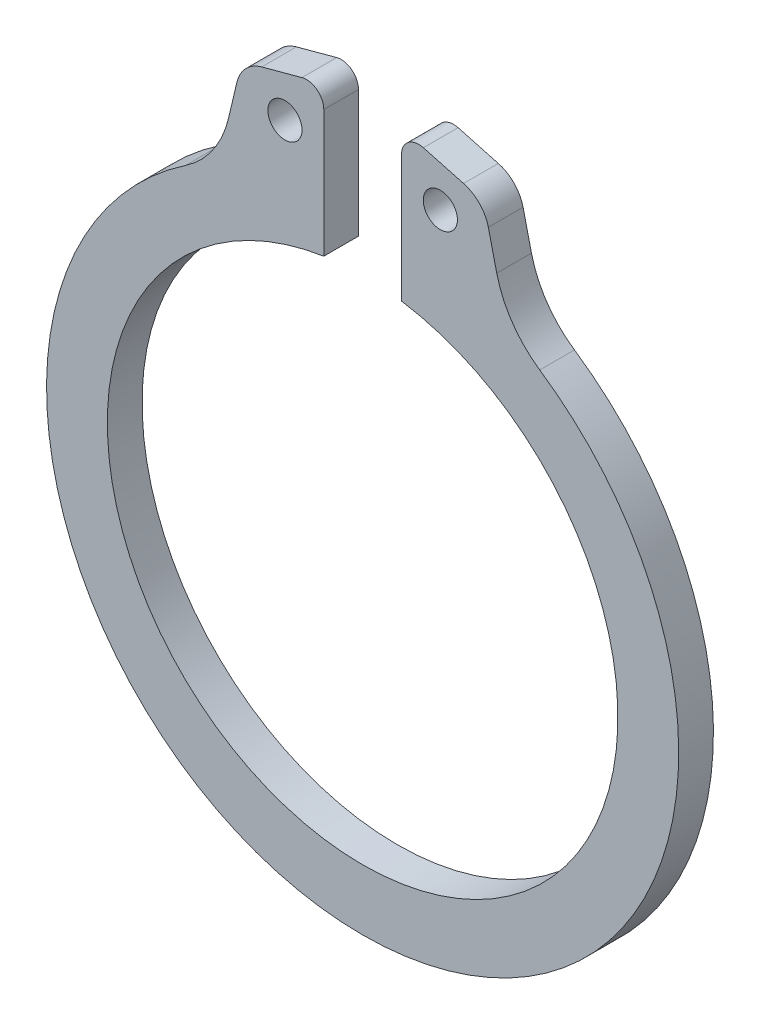
SolidWorks part; units mm, degrees
ref_plane "前视基准面" through (0, 0, 0) normal (0, 0, 1) x (1, 0, 0)
ref_plane "上视基准面" through (0, 0, 0) normal (0, 1, 0) x (1, 0, 0)
ref_plane "右视基准面" through (0, 0, 0) normal (1, 0, 0) x (0, 0, -1)
sketch "草图1" plane through (0, 0, 0) normal (0, 0, 1) x (1, 0, 0)
  line L1 (1.7488, 11.4029) -> (2.2368, 11.271)
  line L2 (1.1184, 9.031) -> (1.1184, 7.2644)
  line L3 (2.2368, 11.271) -> (2.9065, 11.0901)
  line L4 (-1.1184, 10.9202) -> (-1.1184, 9.031)
  line L5 (3.6188, 10.3549) -> (3.861, 9.3311)
  line L6 (1.1184, 10.9202) -> (1.1184, 9.031)
  line L7 (-3.6188, 10.3549) -> (-3.861, 9.3311)
  line L8 (-2.2368, 11.271) -> (-2.9065, 11.0901)
  line L9 (-1.1184, 9.031) -> (-1.1184, 7.2644)
  line L10 (-1.7488, 11.4029) -> (-2.2368, 11.271)
  arc A0 (-1.1184, 7.2644) -> (1.1184, 7.2644) centre (0, 0) ccw
  arc A1 (-5.0994, 7.537) -> (5.0994, 7.537) centre (0, 0) ccw
  circle A2 centre (2.2368, 10.0959) radius 0.4917
  circle A3 centre (-2.2368, 10.0959) radius 0.4917
  arc A4 (5.0994, 7.537) -> (3.861, 9.3311) centre (6.7805, 10.0217) cw
  arc A5 (-5.0994, 7.537) -> (-3.861, 9.3311) centre (-6.7805, 10.0217) ccw
  arc A6 (3.6188, 10.3549) -> (2.9065, 11.0901) centre (2.6457, 10.1247) ccw
  arc A7 (-2.9065, 11.0901) -> (-3.6188, 10.3549) centre (-2.6457, 10.1247) ccw
  arc A8 (1.1184, 10.9202) -> (1.7488, 11.4029) centre (1.6184, 10.9202) cw
  arc A9 (-1.1184, 10.9202) -> (-1.7488, 11.4029) centre (-1.6184, 10.9202) ccw
  dimension "D1" = 18.2
  dimension "D2" = 14.7
  dimension "D3" = 3
  dimension "D4" = 1
  dimension "D5" = 0.5
extrude "凸台-拉伸1" add sketch "草图1" along normal blind 1
